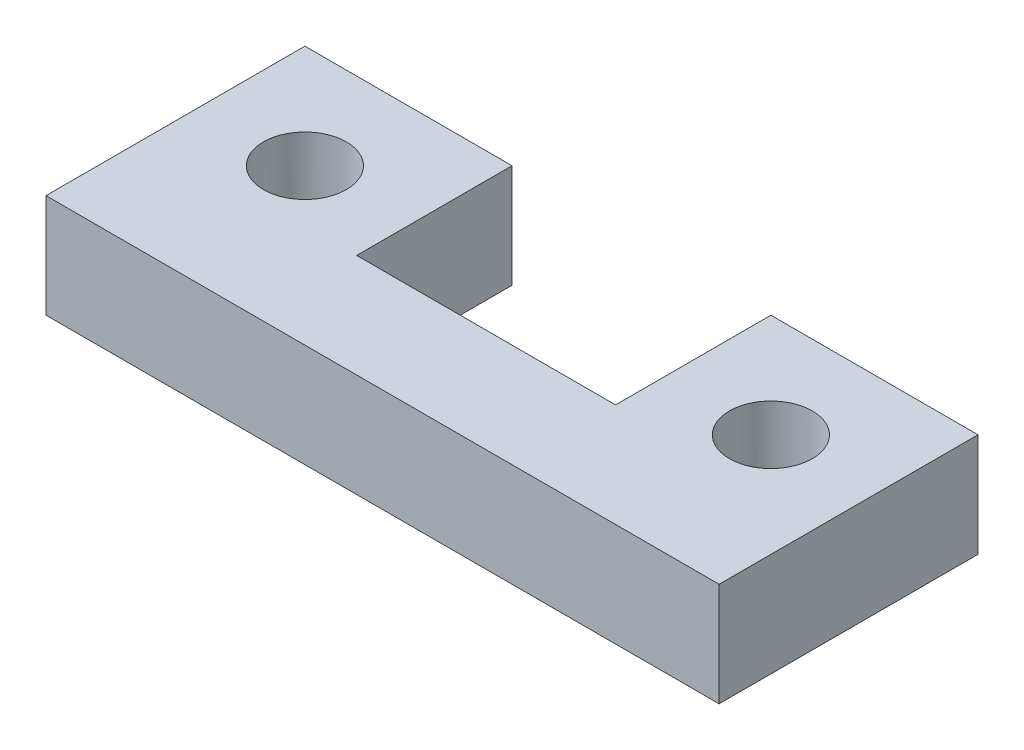
SolidWorks part; units mm, degrees
ref_plane "Front Plane" through (0, 0, 0) normal (0, 0, 1) x (1, 0, 0)
ref_plane "Top Plane" through (0, 0, 0) normal (0, 1, 0) x (1, 0, 0)
ref_plane "Right Plane" through (0, 0, 0) normal (1, 0, 0) x (0, 0, -1)
sketch "Sketch1" plane through (0, 0, 0) normal (0, 1, 0) x (1, 0, 0)
  line L0 (0, 0) -> (0, 30.0943) construction
  line L1 (32.5, 0) -> (-32.5, 0)
  line L2 (-32.5, 0) -> (-32.5, 25)
  line L3 (-32.5, 25) -> (-12.5, 25)
  line L4 (-12.5, 25) -> (-12.5, 10)
  line L5 (-12.5, 10) -> (12.5, 10)
  line L6 (12.5, 25) -> (12.5, 10)
  line L7 (32.5, 25) -> (12.5, 25)
  line L8 (32.5, 0) -> (32.5, 25)
  point P9 (0, 10)
  dimension "D1" = 65
  dimension "D2" = 25
  dimension "D3" = 25
  dimension "D4" = 15
extrude "Boss-Extrude1" add sketch "Sketch1" along normal mid plane 10
sketch "Sketch2" plane through (0, 5, 0) normal (0, 1, 0) x (1, 0, 0)
  line L0 (-22.5, 25) -> (-22.5, 0) construction
  line L1 (-12.5, 25) -> (-32.5, 25) construction
  line L2 (-32.5, 0) -> (32.5, 0) construction
  circle A0 centre (-22.5, 15) radius 4
  dimension "D1" = 8
  dimension "D2" = 10
extrude "Cut-Extrude1" cut sketch "Sketch2" against normal through all both and the other way through all
mirror "Mirror1" about plane through (0, 0, 0) normal (1, 0, 0) of "Cut-Extrude1"
